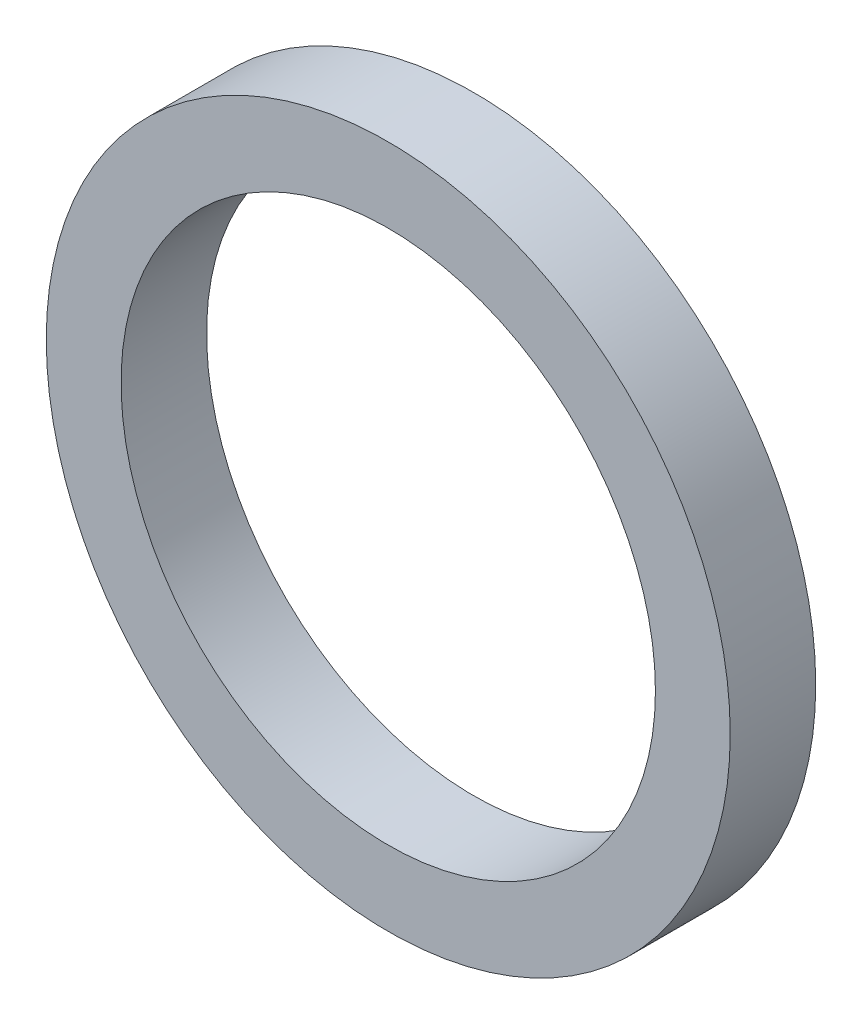
SolidWorks part; units mm, degrees
ref_plane "前视基准面" through (0, 0, 0) normal (0, 0, 1) x (1, 0, 0)
ref_plane "上视基准面" through (0, 0, 0) normal (0, 1, 0) x (1, 0, 0)
ref_plane "右视基准面" through (0, 0, 0) normal (1, 0, 0) x (0, 0, -1)
sketch "草图1" plane through (0, 0, 0) normal (0, 0, 1) x (1, 0, 0)
  circle A0 centre (0, 0) radius 12.5
  circle A1 centre (0, 0) radius 16
  dimension "D1" = 25
  dimension "D2" = 32
extrude "凸台-拉伸1" add sketch "草图1" along normal blind 4
